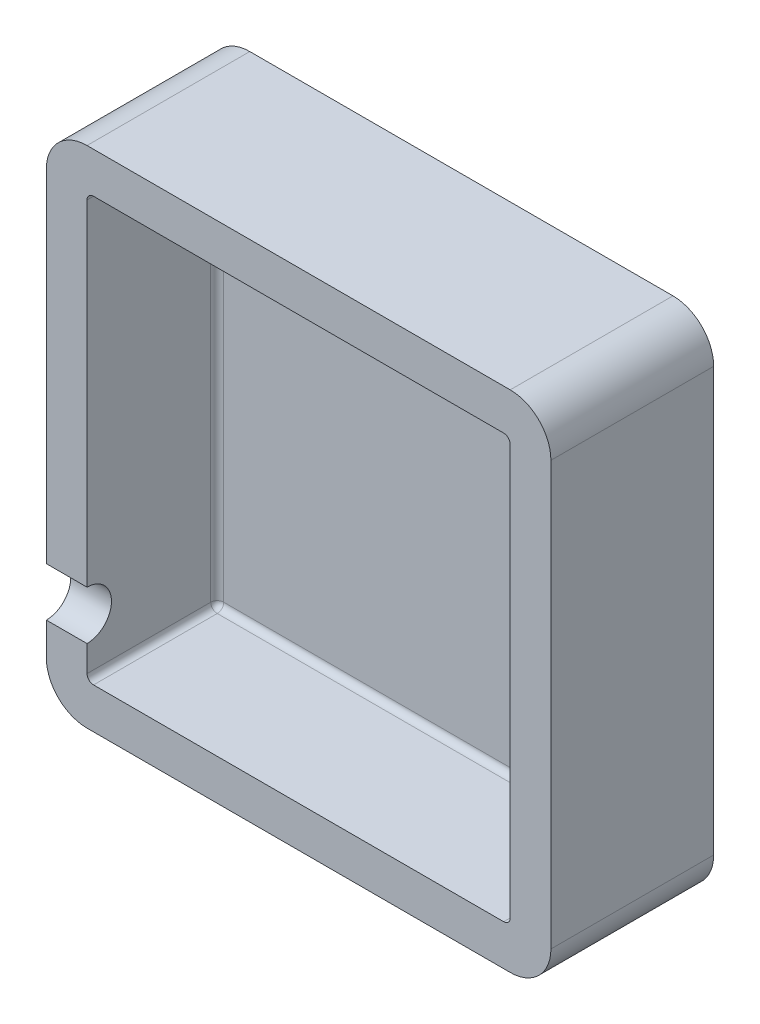
SolidWorks part; units mm, degrees
ref_plane "Piano frontale" through (0, 0, 0) normal (0, 0, 1) x (1, 0, 0)
ref_plane "Piano superiore" through (0, 0, 0) normal (0, 1, 0) x (1, 0, 0)
ref_plane "Piano destro" through (0, 0, 0) normal (1, 0, 0) x (0, 0, -1)
sketch "Schizzo1" plane through (0, 0, 0) normal (0, 0, 1) x (1, 0, 0)
  line L1 (13, -13) -> (-13, -13)
  line L2 (13, -13) -> (13, 13)
  line L3 (13, 13) -> (-13, 13)
  line L4 (-13, -13) -> (-13, 13)
  line L5 (13, -13) -> (-13, 13) construction
  line L6 (13, 13) -> (-13, -13) construction
  point P0 (0, 0)
  dimension "D1" = 26
  dimension "D2" = 26
extrude "Estrusione-Sottile1" add sketch "Schizzo1" along normal blind 8 thin thin type one direction wall 2.5
sketch "Schizzo2" plane through (0, 0, 0) normal (0, 0, -1) x (-1, 0, 0)
  line L1 (-15.5, 15.5) -> (15.5, 15.5)
  line L2 (-15.5, 15.5) -> (-15.5, -15.5)
  line L3 (-15.5, -15.5) -> (15.5, -15.5)
  line L4 (15.5, 15.5) -> (15.5, -15.5)
extrude "Estrusione-Estrusione1" add sketch "Schizzo2" along normal blind 2
fillet "Raccordo1" radius 2.5 4 edges at (-15.5, 15.5, 3) (15.5, 15.5, 3) (15.5, -15.5, 3) (-15.5, -15.5, 3)
fillet "Raccordo2" radius 0.4 8 edges at (-13, 0, 0) (0, 13, 0) (13, 0, 0) (0, -13, 0) (-13, -13, 4) (13, -13, 4) (13, 13, 4) (-13, 13, 4)
sketch "Schizzo3" plane through (-15.5, 0, 0) normal (-1, 0, 0) x (0, 0, 1)
  line L0 (8, 13) -> (8, -13) construction
  circle A0 centre (8, -9.5) radius 1.5
  dimension "D2" = 3
  dimension "D1" = 6
extrude "Taglio-Estrusione1" cut sketch "Schizzo3" against normal up to next
